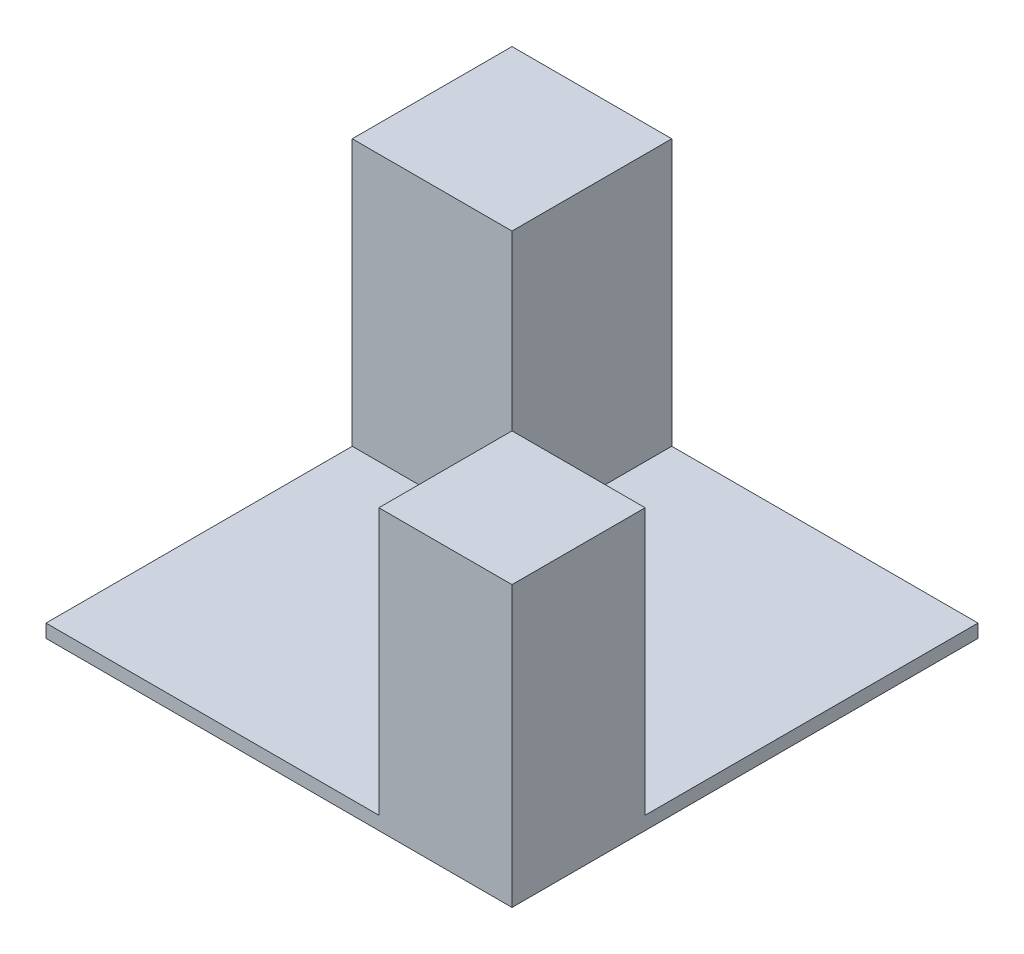
SolidWorks part; units mm, degrees
ref_plane "Front Plane" through (0, 0, 0) normal (0, 0, 1) x (1, 0, 0)
ref_plane "Top Plane" through (0, 0, 0) normal (0, 1, 0) x (1, 0, 0)
ref_plane "Right Plane" through (0, 0, 0) normal (1, 0, 0) x (0, 0, -1)
sketch "Sketch1" plane through (0, 0, 0) normal (0, 1, 0) x (1, 0, 0)
  line L1 (0, 0) -> (35, 0)
  line L2 (0, 0) -> (0, 35)
  line L3 (0, 35) -> (35, 35)
  line L4 (35, 0) -> (35, 35)
  dimension "D1" = 35
extrude "Boss-Extrude1" add sketch "Sketch1" along normal blind 1
sketch "Sketch2" plane through (0, 1, 0) normal (0, 1, 0) x (1, 0, 0)
  line L1 (0, 35) -> (12, 35)
  line L2 (0, 35) -> (0, 23)
  line L3 (0, 23) -> (12, 23)
  line L4 (12, 35) -> (12, 23)
  line L5 (35, 0) -> (25, 0)
  line L6 (35, 0) -> (35, 10)
  line L7 (35, 10) -> (25, 10)
  line L8 (25, 0) -> (25, 10)
  dimension "D1" = 12
  dimension "D2" = 10
extrude "Boss-Extrude2" add sketch "Sketch2" along normal blind 20
